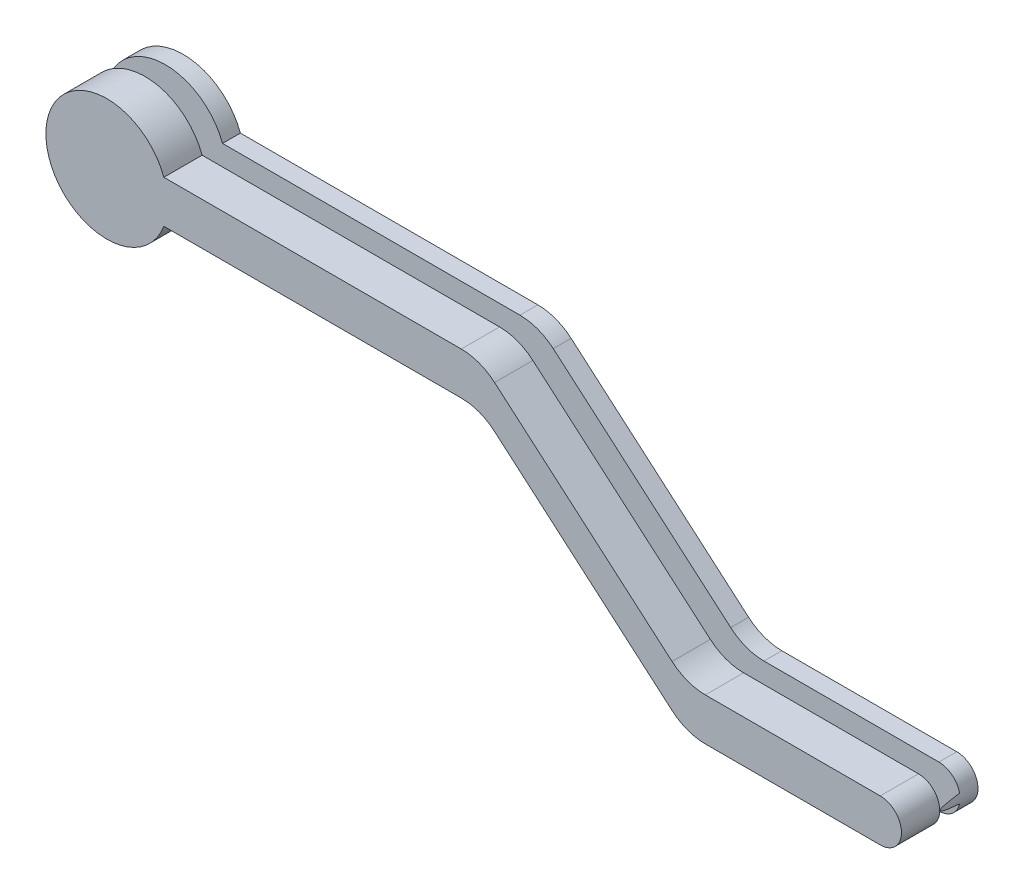
SolidWorks part; units mm, degrees
ref_plane "前视基准面" through (0, 0, 0) normal (0, 0, 1) x (1, 0, 0)
ref_plane "上视基准面" through (0, 0, 0) normal (0, 1, 0) x (1, 0, 0)
ref_plane "右视基准面" through (0, 0, 0) normal (1, 0, 0) x (0, 0, -1)
other "Configuration Table"
sketch "草图1" plane through (0, 0, 0) normal (0, 0, 1) x (1, 0, 0)
  line L0 (0, 0) -> (73.2963, 0) construction
  line L2 (11.1872, -4.1618) -> (69.487, -4.1618)
  line L3 (11.1872, 4.1618) -> (69.487, 4.1618)
  line L4 (76.0128, 1.7389) -> (110.7927, -28.215)
  line L5 (76.0128, -6.5846) -> (110.7927, -36.5385)
  line L6 (117.3185, -30.6378) -> (151.6009, -30.6378)
  line L7 (117.3185, -38.9613) -> (151.6009, -38.9613)
  arc A0 (11.1872, 4.1618) -> (11.1872, -4.1618) centre (0, 0) ccw
  arc A1 (76.0128, 1.7389) -> (69.487, 4.1618) centre (69.487, -5.8382) ccw
  arc A2 (76.0128, -6.5846) -> (69.487, -4.1618) centre (69.487, -14.1618) ccw
  arc A3 (117.3185, -30.6378) -> (110.7927, -28.215) centre (117.3185, -20.6378) cw
  arc A4 (117.3185, -38.9613) -> (110.7927, -36.5385) centre (117.3185, -28.9613) cw
  arc A5 (151.6009, -30.6378) -> (151.6009, -38.9613) centre (151.6009, -34.7995) cw
  point P14 (73.1997, 4.1618)
  point P17 (73.1997, -4.1618)
  point P20 (113.6058, -30.6378)
  point P23 (113.6058, -38.9613)
  dimension "D1" = 10
  dimension "D2" = 10
  dimension "D3" = 10
  dimension "D4" = 10
extrude "凸台-拉伸1" add sketch "草图1" along normal blind 15
sketch "草图4" plane through (0, 4.1618, 0) normal (0, 1, 0) x (1, 0, 0)
  line L0 (-11.9362, -3.5034) -> (155.6602, -3.5034)
  line L1 (-11.9362, 0) -> (-11.9362, -15) construction
  line L2 (-11.9362, -7.5) -> (155.7627, -7.5)
  line L3 (155.7627, -15) -> (155.7627, 0) construction
  line L4 (-11.9362, -3.5034) -> (-11.9362, -7.5)
  line L5 (155.6602, -3.5034) -> (155.7627, -7.5)
extrude "切除-拉伸1" cut sketch "草图4" against normal through all both and the other way through all
sketch "草图6" plane through (0, 0, 15) normal (0, 0, 1) x (1, 0, 0)
  circle A0 centre (27.2496, 0) radius 3.8595
  circle A1 centre (62.4718, 0) radius 3.8198
  circle A2 centre (80.681, -6.3651) radius 2.8699
  circle A3 centre (104.8271, -27.2326) radius 2.8255
  circle A4 centre (125.5758, -34.7504) radius 3.9035
sketch "草图7" plane through (0, 0, 15) normal (0, 0, 1) x (1, 0, 0)
  line L0 (69.487, 4.1618) -> (11.1872, 4.1618) construction
  line L1 (23.5349, 4.1618) -> (31.3716, 4.1618)
  line L2 (23.5349, 4.1618) -> (23.5349, -4.1618)
  line L3 (23.5349, -4.1618) -> (31.3716, -4.1618)
  line L4 (31.3716, 4.1618) -> (31.3716, -4.1618)
  line L5 (11.1872, -4.1618) -> (69.487, -4.1618) construction
  line L6 (81.212, -2.7388) -> (77.0963, -7.5177)
  line L7 (58.3742, 4.1618) -> (66.4239, 4.1618)
  line L8 (58.3742, 4.1618) -> (58.3742, -4.1618)
  line L9 (58.3742, -4.1618) -> (66.4239, -4.1618)
  line L10 (66.4239, 4.1618) -> (66.4239, -4.1618)
  line L11 (110.7927, -28.215) -> (76.0128, 1.7389) construction
  line L12 (76.0128, -6.5846) -> (110.7927, -36.5385) construction
  line L13 (77.0963, -7.5177) -> (80.3559, -10.325)
  line L14 (80.3559, -10.325) -> (84.4716, -5.5461)
  line L15 (84.4716, -5.5461) -> (81.212, -2.7388)
  line L16 (105.0077, -23.2327) -> (100.892, -28.0116)
  line L17 (100.892, -28.0116) -> (104.5191, -31.1354)
  line L18 (104.5191, -31.1354) -> (108.6348, -26.3566)
  line L19 (108.6348, -26.3566) -> (105.0077, -23.2327)
  line L20 (121.6642, -30.6378) -> (121.6642, -38.9613)
  line L21 (151.6009, -30.6378) -> (117.3185, -30.6378) construction
  line L22 (117.3185, -38.9613) -> (151.6009, -38.9613) construction
  line L23 (121.6642, -38.9613) -> (128.9898, -38.9613)
  line L24 (128.9898, -38.9613) -> (128.9898, -30.6378)
  line L25 (128.9898, -30.6378) -> (121.6642, -30.6378)
sketch "草图8" plane through (0, 0, 7.5) normal (0, 0, -1) x (-1, 0, 0)
  line L0 (-31.3716, 4.1618) -> (-31.3716, -4.1618)
  line L1 (-31.3716, -4.1618) -> (-23.5349, -4.1618)
  line L2 (-23.5349, -4.1618) -> (-23.5349, 4.1618)
  line L3 (-23.5349, 4.1618) -> (-31.3716, 4.1618)
  line L4 (-66.4239, 4.1618) -> (-66.4239, -4.1618)
  line L5 (-66.4239, -4.1618) -> (-58.3742, -4.1618)
  line L6 (-58.3742, -4.1618) -> (-58.3742, 4.1618)
  line L7 (-58.3742, 4.1618) -> (-66.4239, 4.1618)
  line L8 (-84.4716, -5.5461) -> (-80.3559, -10.325)
  line L9 (-80.3559, -10.325) -> (-77.0963, -7.5177)
  line L10 (-77.0963, -7.5177) -> (-81.212, -2.7388)
  line L11 (-81.212, -2.7388) -> (-84.4716, -5.5461)
  line L12 (-108.6348, -26.3566) -> (-104.5191, -31.1354)
  line L13 (-104.5191, -31.1354) -> (-100.892, -28.0116)
  line L14 (-100.892, -28.0116) -> (-105.0077, -23.2327)
  line L15 (-105.0077, -23.2327) -> (-108.6348, -26.3566)
  line L16 (-128.9898, -30.6378) -> (-128.9898, -38.9613)
  line L17 (-128.9898, -38.9613) -> (-121.6642, -38.9613)
  line L18 (-121.6642, -38.9613) -> (-121.6642, -30.6378)
  line L19 (-121.6642, -30.6378) -> (-128.9898, -30.6378)
